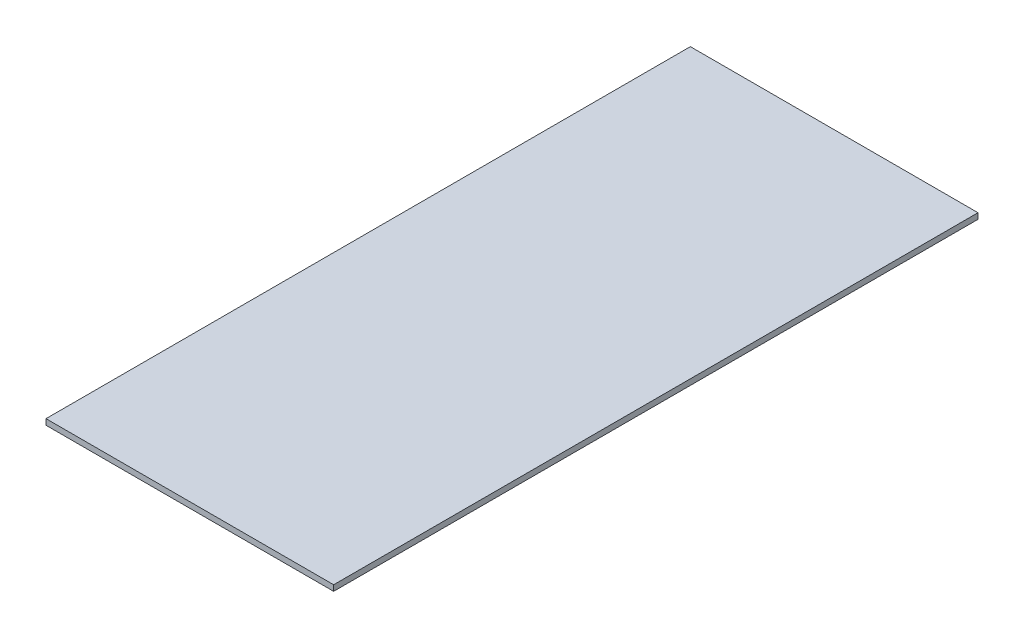
SolidWorks part; units mm, degrees
ref_plane "Front Plane" through (0, 0, 0) normal (0, 0, 1) x (1, 0, 0)
ref_plane "Top Plane" through (0, 0, 0) normal (0, 1, 0) x (1, 0, 0)
ref_plane "Right Plane" through (0, 0, 0) normal (1, 0, 0) x (0, 0, -1)
sketch "Sketch1" plane through (0, 0, 0) normal (0, 1, 0) x (1, 0, 0)
  line L1 (0, 0) -> (158.75, 0)
  line L2 (0, 0) -> (0, 355.6)
  line L3 (0, 355.6) -> (158.75, 355.6)
  line L4 (158.75, 0) -> (158.75, 355.6)
  point P7 (92.9773, 282.0845)
  dimension "D1" = 158.75
  dimension "D2" = 355.6
extrude "Boss-Extrude1" add sketch "Sketch1" along normal blind 3.175
